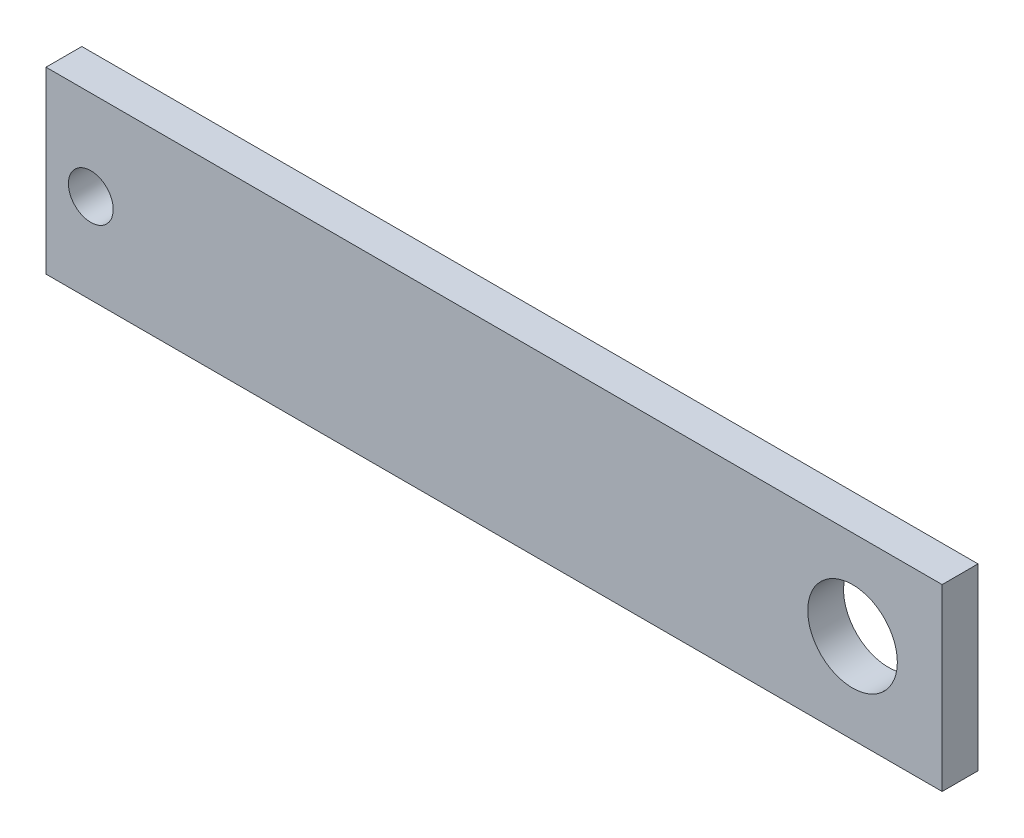
SolidWorks part; units mm, degrees
material "Plastique personnalisé"
ref_plane "Plan de face" through (0, 0, 0) normal (0, 0, 1) x (1, 0, 0)
ref_plane "Plan de dessus" through (0, 0, 0) normal (0, 1, 0) x (1, 0, 0)
ref_plane "Plan de droite" through (0, 0, 0) normal (1, 0, 0) x (0, 0, -1)
sketch "Esquisse1" plane through (0, 0, 0) normal (0, 0, 1) x (1, 0, 0)
  line L1 (0, 0) -> (100, 0)
  line L2 (0, 0) -> (0, 20)
  line L3 (0, 20) -> (100, 20)
  line L4 (100, 0) -> (100, 20)
  line L5 (0, 0) -> (100, 20) construction
  line L6 (0, 20) -> (100, 0) construction
  circle A0 centre (5, 10) radius 2.5
  circle A1 centre (90, 10) radius 5
  point P4 (50, 10)
  dimension "D3" = 5
  dimension "D4" = 10
  dimension "D1" = 100
  dimension "D2" = 20
  dimension "D5" = 10
  dimension "D6" = 10
  dimension "D7" = 5
extrude "Boss.-Extru.1" add sketch "Esquisse1" along normal blind 4
